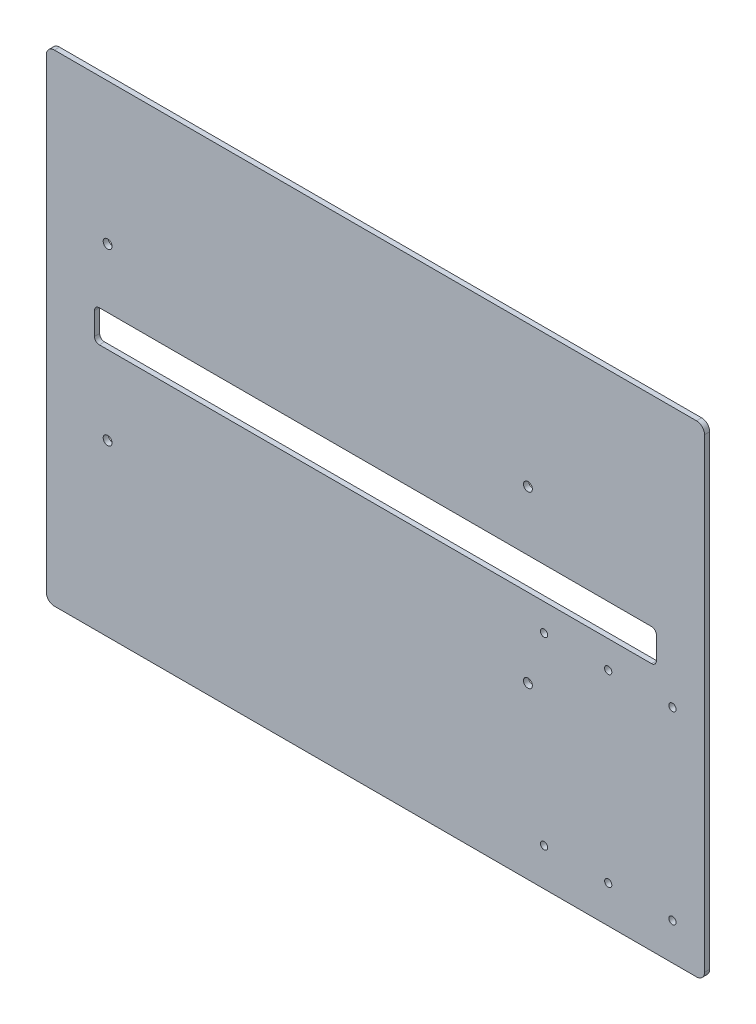
SolidWorks part; units mm, degrees
ref_plane "Front Plane" through (0, 0, 0) normal (0, 0, 1) x (1, 0, 0)
ref_plane "Top Plane" through (0, 0, 0) normal (0, 1, 0) x (1, 0, 0)
ref_plane "Right Plane" through (0, 0, 0) normal (1, 0, 0) x (0, 0, -1)
sketch "Sketch1" plane through (0, 0, 0) normal (0, 0, 1) x (1, 0, 0)
  line L0 (390, 0) -> (390, 300) construction
  line L1 (5, 0) -> (405, 0)
  line L2 (0, 5) -> (0, 295)
  line L3 (5, 300) -> (405, 300)
  line L4 (410, 5) -> (410, 295)
  line L5 (350, 0) -> (350, 300) construction
  line L6 (310, 0) -> (310, 300) construction
  line L7 (0, 106) -> (410, 106) construction
  line L8 (310, 23.3394) -> (410, 22.8831) construction
  line L9 (390, 137.9743) -> (310, 137.9743) construction
  line L10 (0, 212) -> (410, 212) construction
  line L11 (38.17, 106) -> (38.17, 212) construction
  line L12 (300, 106) -> (300, 212) construction
  line L13 (0, 155) -> (410, 155) construction
  line L15 (33, 155) -> (377, 155)
  line L16 (30, 158) -> (30, 172)
  line L17 (33, 175) -> (377, 175)
  line L18 (380, 158) -> (380, 172)
  circle A0 centre (310, 23.3394) radius 2.25
  circle A1 centre (350, 23.1569) radius 2.25
  circle A2 centre (390, 22.9743) radius 2.25
  circle A3 centre (310, 137.9743) radius 2.25
  circle A4 centre (350, 137.9743) radius 2.25
  circle A5 centre (390, 137.9743) radius 2.25
  circle A6 centre (300, 106) radius 2.75
  circle A7 centre (38.17, 106) radius 2.75
  circle A8 centre (38.17, 212) radius 2.75
  circle A9 centre (300, 212) radius 2.75
  arc A10 (5, 0) -> (0, 5) centre (5, 5) cw
  arc A11 (405, 0) -> (410, 5) centre (405, 5) ccw
  arc A12 (405, 300) -> (410, 295) centre (405, 295) cw
  arc A13 (0, 295) -> (5, 300) centre (5, 295) cw
  arc A14 (377, 155) -> (380, 158) centre (377, 158) ccw
  arc A15 (377, 175) -> (380, 172) centre (377, 172) cw
  arc A16 (33, 155) -> (30, 158) centre (33, 158) cw
  arc A17 (30, 172) -> (33, 175) centre (33, 172) cw
  point P40 (0, 0)
  point P45 (410, 300)
  point P48 (0, 300)
  point P56 (380, 155)
  point P59 (380, 175)
  point P62 (30, 155)
  dimension "D7" = 300
  dimension "D8" = 115
  dimension "D9" = 38.17
  dimension "D10" = 106
  dimension "D11" = 5
  dimension "D12" = 5.5
  dimension "D13" = 4.5
  dimension "D18" = 3
  dimension "D1" = 300
  dimension "D2" = 410
  dimension "D3" = 40
  dimension "D4" = 40
  dimension "D5" = 20
  dimension "D6" = 106
  dimension "D14" = 155
  dimension "D15" = 30
  dimension "D16" = 30
  dimension "D17" = 20
extrude "Boss-Extrude1" add sketch "Sketch1" along normal blind 3.2 contours L2 A13 L3 A12 L4 A11 L1 A10
